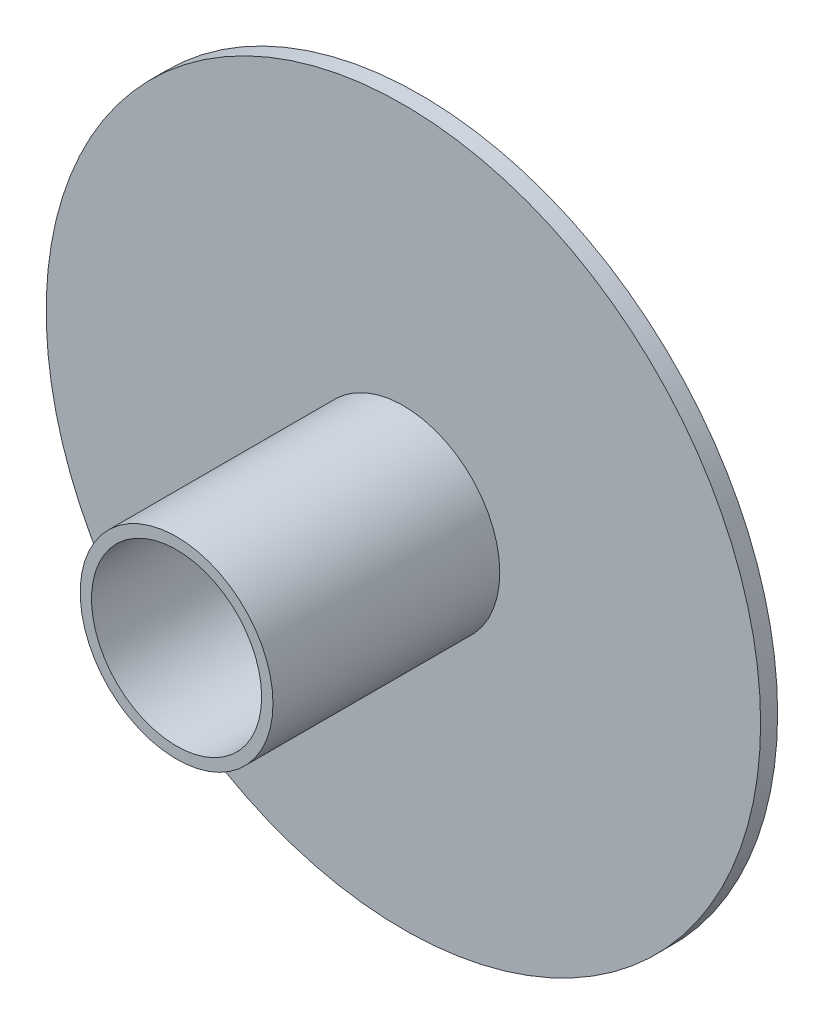
SolidWorks part; units mm, degrees
ref_plane "Front" through (0, 0, 0) normal (0, 0, 1) x (1, 0, 0)
ref_plane "Top" through (0, 0, 0) normal (0, 1, 0) x (1, 0, 0)
ref_plane "Right" through (0, 0, 0) normal (1, 0, 0) x (0, 0, -1)
sketch "Sketch1" plane through (0, 0, 0) normal (0, 0, 1) x (1, 0, 0)
  circle A0 centre (0, 0) radius 30 construction
  circle A1 centre (0, 0) radius 31.5
  dimension "D1" = 60
  dimension "D2" = 1.5
extrude "Boss-Extrude1" add sketch "Sketch1" along normal blind 1.5 contours A1
sketch "Sketch2" plane through (0, 0, 1.5) normal (0, 0, 1) x (1, 0, 0)
  circle A0 centre (0, 0) radius 7.5 construction
  circle A1 centre (0, 0) radius 8.5
  dimension "D1" = 15
  dimension "D2" = 1
extrude "Boss-Extrude2" add sketch "Sketch2" along normal blind 20
sketch "Sketch3" plane through (0, 0, 21.5) normal (0, 0, 1) x (1, 0, 0)
  circle A0 centre (0, 0) radius 7.5
  dimension "D1" = 15
extrude "Cut-Extrude1" cut sketch "Sketch3" against normal through all both and the other way through all contours A0
equation "\"D1@Sketch1\"=\"Cavity_Diameter\""
equation "\"Wall_Thickness\"= 1.5"
equation "\"Cavity_Diameter\"= 60"
equation "\"D2@Sketch1\"=\"Wall_Thickness\""
equation "\"D1@Boss-Extrude1\"=\"Wall_Thickness\""
equation "\"Outlet_Diameter\" = 15"
equation "\"D1@Sketch2\"=\"Outlet_Diameter\""
equation "\"Outlet_Length\"= 20"
equation "\"D1@Boss-Extrude2\"=\"Outlet_Length\""
equation "\"D1@Sketch3\"=\"Outlet_Diameter\""
